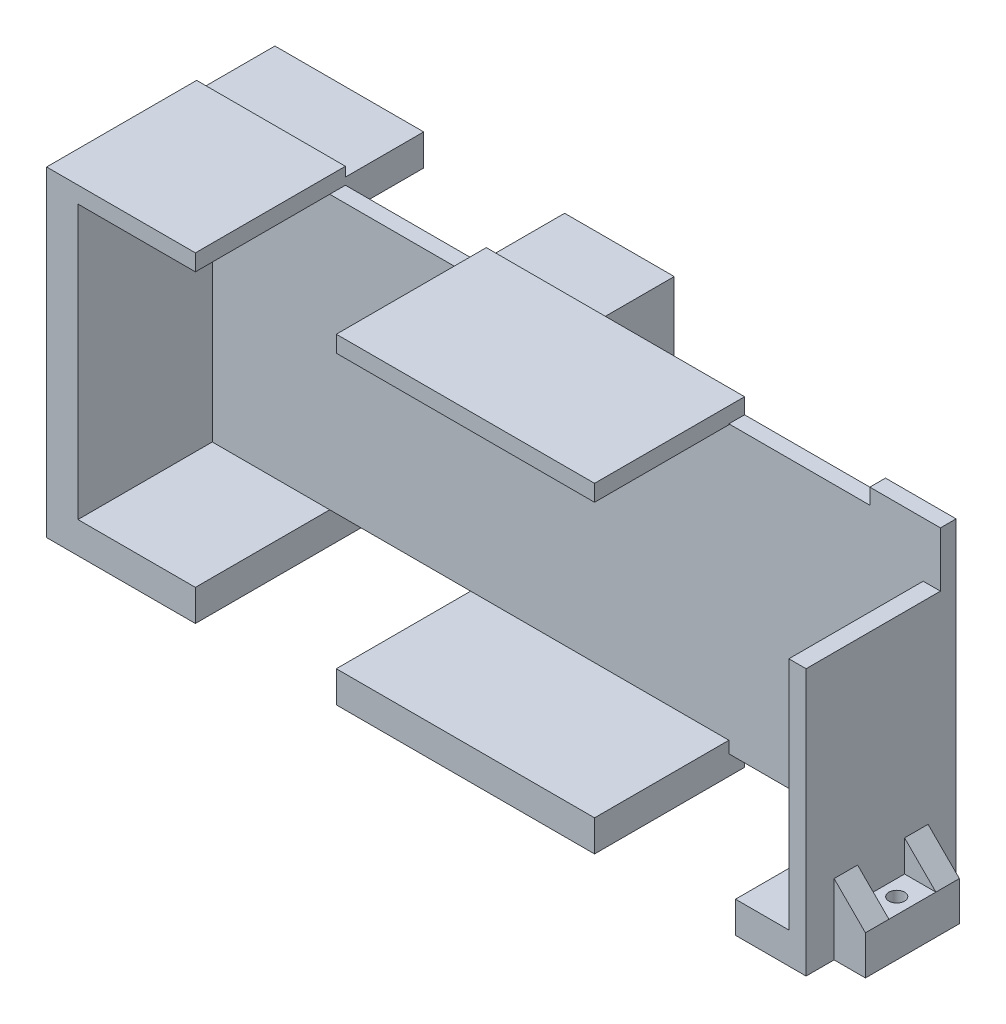
SolidWorks part; units mm, degrees
material "ABS"
ref_plane "Front Plane" through (0, 0, 0) normal (0, 0, 1) x (1, 0, 0)
ref_plane "Top Plane" through (0, 0, 0) normal (0, 1, 0) x (1, 0, 0)
ref_plane "Right Plane" through (0, 0, 0) normal (1, 0, 0) x (0, 0, -1)
sketch "Sketch1" plane through (0, 0, 0) normal (0, 0, 1) x (1, 0, 0)
  line L1 (29.337, -20.193) -> (-29.337, -20.193)
  line L2 (29.337, -20.193) -> (29.337, 20.193)
  line L3 (29.337, 20.193) -> (-29.337, 20.193)
  line L4 (-29.337, -20.193) -> (-29.337, 20.193)
  line L5 (29.337, -20.193) -> (-29.337, 20.193) construction
  line L6 (29.337, 20.193) -> (-29.337, -20.193) construction
  line L7 (32.385, 25.273) -> (-32.385, 25.273)
  line L8 (32.385, 25.273) -> (32.385, -25.273)
  line L9 (32.385, -25.273) -> (-32.385, -25.273)
  line L10 (-32.385, 25.273) -> (-32.385, -25.273)
  line L11 (32.385, 25.273) -> (-32.385, -25.273) construction
  line L12 (32.385, -25.273) -> (-32.385, 25.273) construction
  point P0 (0, 0)
  point P6 (0, 0)
  dimension "D1" = 40.386
  dimension "D2" = 58.674
  dimension "D3" = 3.048
  dimension "D4" = 5.08
extrude "Boss-Extrude1" add sketch "Sketch1" along normal blind 12.7
sketch "Sketch3" plane through (0, 0, 12.7) normal (0, 0, 1) x (1, 0, 0)
  line L0 (79.354, -25.273) -> (79.354, -22.098)
  line L1 (-32.385, -25.273) -> (56.494, -25.273)
  line L2 (-32.385, -25.273) -> (-32.385, 26.797)
  line L3 (-32.385, 26.797) -> (56.494, 26.797)
  line L4 (90.805, -25.273) -> (90.805, 26.797)
  line L5 (79.354, -22.098) -> (56.494, -22.098)
  line L6 (56.494, -22.098) -> (56.494, -25.273)
  line L7 (79.354, -25.273) -> (90.805, -25.273)
  line L8 (79.354, 26.797) -> (79.354, 24.257)
  line L9 (79.354, 24.257) -> (56.494, 24.257)
  line L10 (56.494, 24.257) -> (56.494, 26.797)
  line L11 (79.354, 26.797) -> (90.805, 26.797)
  dimension "D1" = 123.19
  dimension "D2" = 52.07
  dimension "D3" = 3.175
  dimension "D4" = 22.86
  dimension "D5" = 11.451
  dimension "D6" = 22.86
  dimension "D7" = 2.54
extrude "Boss-Extrude2" add sketch "Sketch3" along normal blind 2.54
sketch "Sketch5" plane through (0, 0, 15.24) normal (0, 0, 1) x (1, 0, 0)
  line L0 (-32.385, 26.797) -> (-32.385, -25.273)
  line L1 (-32.385, -25.273) -> (56.494, -25.273)
  line L2 (56.494, -25.273) -> (56.494, -20.193)
  line L3 (56.494, -20.193) -> (79.354, -20.193)
  line L4 (79.354, -20.193) -> (79.354, -25.273)
  line L5 (79.354, -25.273) -> (90.805, -25.273)
  line L6 (90.805, -25.273) -> (90.805, 17.907)
  line L7 (90.805, 26.797) -> (79.354, 26.797) construction
  line L9 (88.011, -20.193) -> (79.354, -20.193)
  line L10 (56.494, 24.13) -> (56.494, 26.797)
  line L11 (56.494, 26.797) -> (-32.385, 26.797)
  line L12 (-27.305, 24.13) -> (-27.305, -20.193)
  line L13 (-27.305, -20.193) -> (56.494, -20.193)
  line L14 (79.354, -25.273) -> (79.354, -20.193)
  line L15 (88.011, -20.193) -> (88.011, 17.907)
  line L17 (56.494, 24.13) -> (-27.305, 24.13)
  line L18 (88.011, 17.907) -> (90.805, 17.907)
  line M7 (-32.385, 26.797) -> (-32.385, -25.273)
  line M8 (-32.385, -25.273) -> (56.494, -25.273)
  line M9 (56.494, -25.273) -> (56.494, -22.098)
  line M11 (79.354, -22.098) -> (79.354, -25.273)
  line M12 (79.354, -25.273) -> (90.805, -25.273)
  line M13 (90.805, -25.273) -> (90.805, 26.797)
  line M17 (56.494, 24.257) -> (56.494, 26.797)
  line M18 (56.494, 26.797) -> (-32.385, 26.797)
  dimension "D1" = 5.08
  dimension "D2" = 2.794
  dimension "D3" = 2.667
  dimension "D4" = 5.08
  dimension "D5" = 8.89
extrude "Boss-Extrude3" add sketch "Sketch5" along normal blind 21.7932 contours L17 L10 L13 L12 M17 M18 M7 M8 M9 | L18 L15 L9 M11 M12 M13
sketch "Sketch6" plane through (0, 0, 37.0332) normal (0, 0, 1) x (1, 0, 0)
  line L1 (-8.255, 26.797) -> (14.605, 26.797)
  line L2 (-8.255, 26.797) -> (-8.255, 24.13)
  line L3 (-8.255, 24.13) -> (14.605, 24.13)
  line L4 (14.605, 26.797) -> (14.605, 24.13)
  line L9 (-8.255, -25.273) -> (-8.255, -20.193)
  line L12 (-8.255, -20.193) -> (14.605, -20.193)
  line L13 (14.605, -20.193) -> (14.605, -25.273)
  line L14 (14.605, -25.273) -> (-8.255, -25.273)
  line L17 (56.494, 26.797) -> (-32.385, 26.797) construction
  line L18 (-32.385, 26.797) -> (-32.385, -25.273) construction
  line L20 (-32.385, -25.273) -> (56.494, -25.273) construction
  line L24 (56.494, 24.13) -> (-27.305, 24.13) construction
  line L25 (-27.305, -20.193) -> (56.494, -20.193) construction
  dimension "D1" = 22.86
  dimension "D2" = 24.13
extrude "Cut-Extrude1" cut sketch "Sketch6" against normal through all
sketch "Sketch7" plane through (0, 0, 0) normal (0, 0, -1) x (-1, 0, 0)
  line L0 (-32.385, 25.273) -> (-14.605, 25.273) construction
  line L1 (-14.605, 25.273) -> (8.255, 25.273)
  line L2 (-14.605, 25.273) -> (-14.605, 20.193)
  line L3 (-14.605, 20.193) -> (8.255, 20.193)
  line L4 (8.255, 25.273) -> (8.255, 20.193)
  line L5 (-29.337, 20.193) -> (29.337, 20.193) construction
  line L6 (29.337, -20.193) -> (8.255, -20.193) construction
  line L7 (-14.605, -20.193) -> (8.255, -20.193)
  line L8 (-14.605, -20.193) -> (-14.605, -21.336)
  line L9 (-14.605, -21.336) -> (8.255, -21.336)
  line L10 (8.255, -20.193) -> (8.255, -21.336)
  line L11 (-14.605, -20.193) -> (-14.605, -25.273) construction
  line L14 (8.255, 26.797) -> (8.255, 25.273) construction
  line L15 (-14.605, 25.273) -> (-14.605, 26.797) construction
extrude "Cut-Extrude2" cut sketch "Sketch7" against normal blind 12.7
sketch "Sketch10" plane through (-32.385, 0, 0) normal (-1, 0, 0) x (0, 0, 1)
  line L0 (18.5166, -25.273) -> (18.5166, -21.2771) construction
  line L1 (37.0332, -25.273) -> (0, -25.273) construction
  line L3 (11.4681, -25.273) -> (25.5651, -25.273)
  line L4 (11.4681, -25.273) -> (11.4681, -18.923)
  line L5 (11.4681, -18.923) -> (25.5651, -18.923)
  line L6 (25.5651, -25.273) -> (25.5651, -18.923)
  dimension "D1" = 14.097
  dimension "D2" = 6.35
extrude "Boss-Extrude4" add sketch "Sketch10" along normal blind 5.08
sketch "Sketch11" plane through (0, 0, 25.5651) normal (0, 0, 1) x (1, 0, 0)
  line L0 (-37.465, -18.923) -> (-32.385, -18.923)
  line L1 (-32.385, -18.923) -> (-32.385, -13.843)
  line L3 (-32.385, -13.843) -> (-37.465, -18.923)
  line L4 (-32.385, 26.797) -> (-32.385, -25.273) construction
extrude "Boss-Extrude5" add sketch "Sketch11" against normal blind 3.81
sketch "Sketch12" plane through (0, -18.923, 0) normal (0, 1, 0) x (1, 0, 0)
  line L0 (-34.925, -11.4681) -> (-34.925, -25.5651) construction
  line L1 (-37.465, -11.4681) -> (-32.385, -11.4681) construction
  line L2 (-32.385, -25.5651) -> (-37.465, -25.5651) construction
  line L3 (-37.465, -18.5166) -> (-32.385, -18.5166) construction
  line L4 (-37.465, -21.7551) -> (-37.465, -11.4681) construction
  line L5 (-32.385, -37.0332) -> (-32.385, -12.7) construction
  circle A0 centre (-34.925, -18.5166) radius 1.27
  dimension "D1" = 2.54
extrude "Cut-Extrude3" cut sketch "Sketch12" against normal through all
sketch "Sketch13" plane through (0, 0, 11.4681) normal (0, 0, -1) x (-1, 0, 0)
  line L0 (32.385, -13.843) -> (32.385, -18.923)
  line L1 (32.385, -18.923) -> (37.465, -18.923)
  line L2 (37.465, -18.923) -> (32.385, -13.843)
extrude "Boss-Extrude7" add sketch "Sketch13" against normal blind 3.81
sketch "Sketch14" plane through (90.805, 0, 0) normal (1, 0, 0) x (0, 0, -1)
  line L0 (-24.8666, -25.273) -> (-24.8666, -9.3209) construction
  line L1 (-37.0332, -25.273) -> (-12.7, -25.273) construction
  line L3 (-32.4866, -25.273) -> (-17.2466, -25.273)
  line L4 (-32.4866, -25.273) -> (-32.4866, -18.923)
  line L5 (-32.4866, -18.923) -> (-17.2466, -18.923)
  line L6 (-17.2466, -25.273) -> (-17.2466, -18.923)
  dimension "D1" = 15.24
  dimension "D2" = 6.35
extrude "Boss-Extrude8" add sketch "Sketch14" along normal blind 5.08
sketch "Sketch15" plane through (0, -18.923, 0) normal (0, 1, 0) x (1, 0, 0)
  line L0 (90.805, -24.8666) -> (95.885, -24.8666) construction
  line L1 (90.805, -17.2466) -> (90.805, -32.4866) construction
  line L2 (95.885, -17.2466) -> (95.885, -32.4866) construction
  line L3 (93.345, -32.4866) -> (93.345, -17.2466) construction
  line L4 (95.885, -32.4866) -> (90.805, -32.4866) construction
  line L5 (95.885, -17.2466) -> (90.805, -17.2466) construction
  circle A0 centre (93.345, -24.8666) radius 1.27
  circle A1 centre (-34.925, -18.5166) radius 1.27 construction
  dimension "D1" = 2.54
  dimension "D2" = 6.35
  dimension "D3" = 128.27
extrude "Cut-Extrude4" cut sketch "Sketch15" against normal through all
sketch "Sketch17" plane through (0, 0, 32.4866) normal (0, 0, 1) x (1, 0, 0)
  line L0 (95.885, -18.923) -> (90.805, -18.923)
  line L1 (90.805, -18.923) -> (90.805, -13.843)
  line L3 (90.805, -25.273) -> (90.805, 17.907) construction
  line L4 (90.805, -13.843) -> (95.885, -18.923)
extrude "Boss-Extrude9" add sketch "Sketch17" against normal blind 3.81
sketch "Sketch18" plane through (0, 0, 17.2466) normal (0, 0, -1) x (-1, 0, 0)
  line L0 (-95.885, -18.923) -> (-90.805, -18.923)
  line L1 (-90.805, -18.923) -> (-90.805, -13.843)
  line L2 (-90.805, -13.843) -> (-95.885, -18.923)
extrude "Boss-Extrude10" add sketch "Sketch18" against normal blind 3.81
